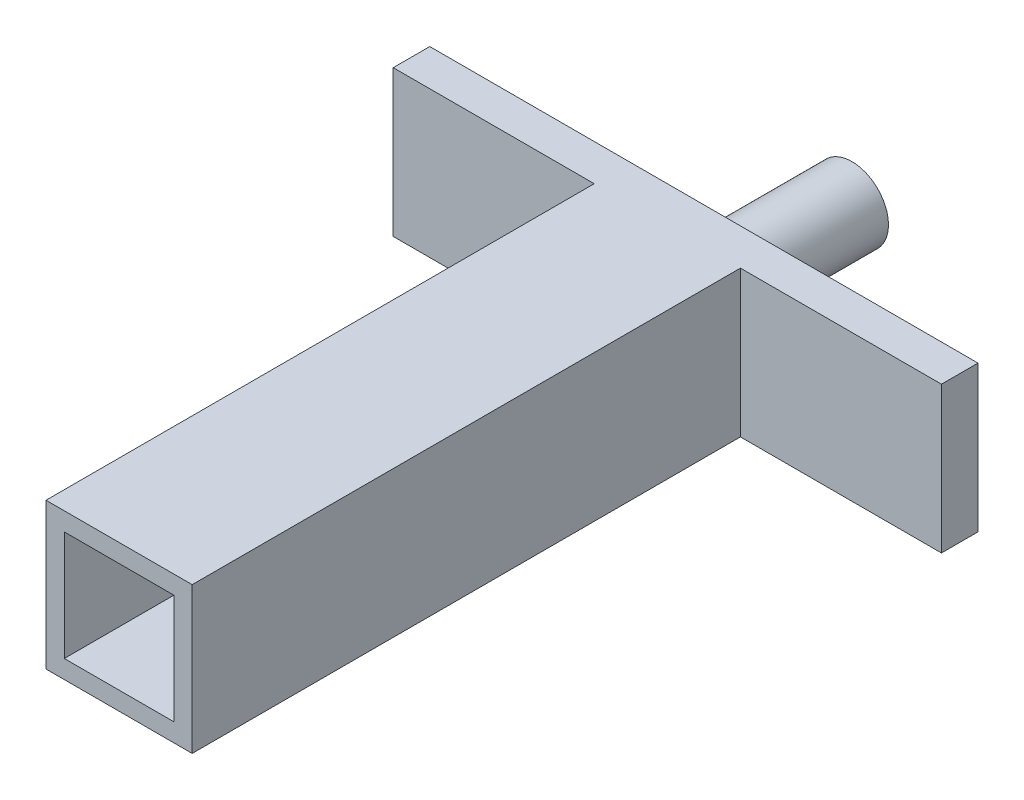
SolidWorks part; units mm, degrees
ref_plane "Front Plane" through (0, 0, 0) normal (0, 0, 1) x (1, 0, 0)
ref_plane "Top Plane" through (0, 0, 0) normal (0, 1, 0) x (1, 0, 0)
ref_plane "Right Plane" through (0, 0, 0) normal (1, 0, 0) x (0, 0, -1)
sketch "Эскиз8" plane through (0, 0, 0) normal (0, 0, 1) x (1, 0, 0)
  line L1 (-2, 2) -> (2, 2)
  line L2 (-2, 2) -> (-2, -2)
  line L3 (-2, -2) -> (2, -2)
  line L4 (2, 2) -> (2, -2)
  line L5 (-2, 2) -> (2, -2) construction
  line L6 (-2, -2) -> (2, 2) construction
  point P0 (0, 0)
  dimension "D1" = 4
  dimension "D2" = 4
extrude "Бобышка-Вытянуть5" add sketch "Эскиз8" along normal blind 16
shell "Оболочка2" thickness 0.5
sketch "Эскиз9" plane through (0, 0, 0) normal (0, 0, -1) x (-1, 0, 0)
  circle A0 centre (0, 0) radius 1
extrude "Бобышка-Вытянуть6" add sketch "Эскиз9" along normal blind 4
sketch "Эскиз10" plane through (0, 0, -4) normal (0, 0, -1) x (-1, 0, 0)
  line L0 (0, -0.5566) -> (0, 0.5566)
  arc A0 (0.1542, -0.6797) -> (0, -0.5566) centre (0.1263, -0.5566) cw
  circle A1 centre (0, 0) radius 1
  arc A2 (0.1542, 0.6797) -> (0.1542, -0.6797) centre (0, 0) cw
  arc A3 (0, 0.5566) -> (0.1542, 0.6797) centre (0.1263, 0.5566) cw
  circle A4 centre (0, 0) radius 0.849
  circle M1 centre (0, 0) radius 1
extrude "Бобышка-Вытянуть7" add sketch "Эскиз10" along normal blind 0.05 contours A4 M1 | A3 L0 A0 A2
sketch "Эскиз11" plane through (0, 0, 0) normal (0, 0, -1) x (-1, 0, 0)
  line L0 (-1, 0) -> (-7.5, 0) construction
  line L1 (-2, 2) -> (-7.5, 2)
  line L2 (-7.5, 2) -> (-7.5, -2)
  line L3 (-7.5, -2) -> (-2, -2)
  line L4 (0, 0) -> (0, 3.2725) construction
  line L5 (0, -0.5566) -> (0, 0.5566) construction
  line L6 (-2, 2) -> (-2, -2)
  line L7 (2, 2) -> (2, -2)
  line L8 (7.5, -2) -> (2, -2)
  line L9 (7.5, 2) -> (7.5, -2)
  line L10 (2, 2) -> (7.5, 2)
  circle A2 centre (0, 0) radius 1 construction
  circle A3 centre (0, 0) radius 1 construction
extrude "Бобышка-Вытянуть8" add sketch "Эскиз11" against normal blind 1
